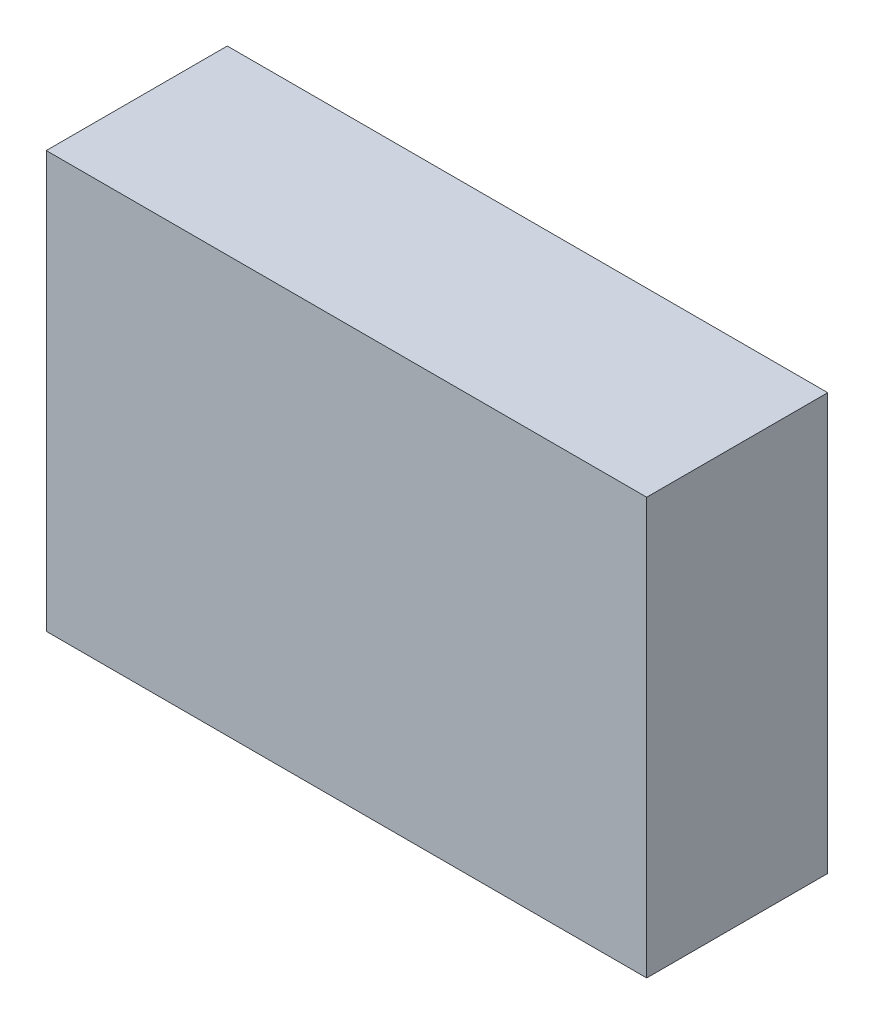
SolidWorks part; units mm, degrees
ref_plane "Front Plane" through (0, 0, 0) normal (0, 0, 1) x (1, 0, 0)
ref_plane "Top Plane" through (0, 0, 0) normal (0, 1, 0) x (1, 0, 0)
ref_plane "Right Plane" through (0, 0, 0) normal (1, 0, 0) x (0, 0, -1)
sketch "Sketch1" plane through (0, 0, 0) normal (0, 0, 1) x (1, 0, 0)
  line L0 (-5.25, 3.7) -> (4.7, 3.7)
  line L1 (4.7, 3.7) -> (4.7, -3.2)
  line L2 (4.7, -3.2) -> (-5.25, -3.2)
  line L3 (-5.25, -3.2) -> (-5.25, 3.7)
extrude "Component_Outline" add sketch "Sketch1" along normal blind 3 separate body
sketch3d "3DSketch1"
  line L0 (0, 0, 0) -> (1, 0, 0)
  line L1 (0, 0, 0) -> (0, 1, 0)
  line L2 (0, 0, 0) -> (0, 0, 1)
  point P0 (0, 0, 0)
